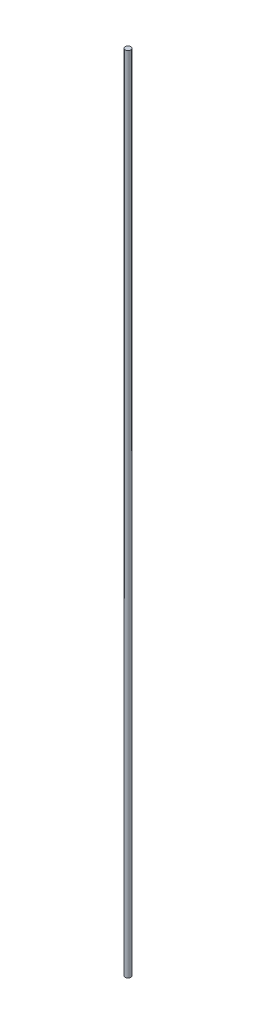
SolidWorks part; units mm, degrees
ref_plane "前视基准面" through (0, 0, 0) normal (0, 0, 1) x (1, 0, 0)
ref_plane "上视基准面" through (0, 0, 0) normal (0, 1, 0) x (1, 0, 0)
ref_plane "右视基准面" through (0, 0, 0) normal (1, 0, 0) x (0, 0, -1)
sketch "草图1" plane through (0, 0, 0) normal (0, 1, 0) x (1, 0, 0)
  circle A0 centre (0, 0) radius 1.75
  dimension "D1" = 3.5
extrude "凸台-拉伸1" add sketch "草图1" along normal blind 500
